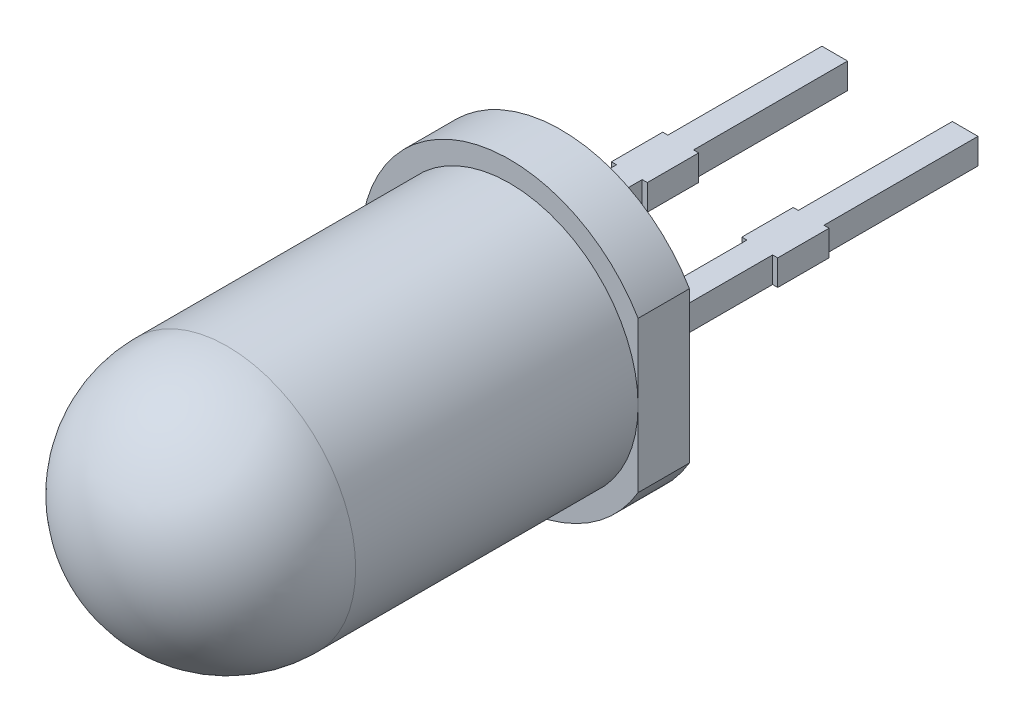
SolidWorks part; units mm, degrees
ref_plane "Front" through (0, 0, 0) normal (0, 0, 1) x (1, 0, 0)
ref_plane "Top" through (0, 0, 0) normal (0, 1, 0) x (1, 0, 0)
ref_plane "Right" through (0, 0, 0) normal (1, 0, 0) x (0, 0, -1)
sketch "Эскиз1" plane through (0, 0, 0) normal (0, -1, 0) x (1, 0, 0)
  line L0 (1.27, 0) -> (-1.27, 0) construction
  line L3 (-1.27, -3) -> (-1.27, 3.6) construction
  line L4 (-1.52, 3.6) -> (-1.52, 1)
  line L5 (-1.52, 1) -> (-1.62, 1)
  line L6 (-1.62, 1) -> (-1.62, 0)
  line L7 (-1.62, 0) -> (-1.52, 0)
  line L8 (-1.52, 0) -> (-1.52, -3)
  line L9 (-1.52, -3) -> (-1.02, -3)
  line L10 (-1.02, 1) -> (-1.02, 0) construction
  line L11 (-1.52, 1) -> (-1.52, 0) construction
  line L12 (-1.02, 0) -> (-1.02, -3)
  line L13 (-0.92, 0) -> (-1.02, 0)
  line L14 (-0.92, 1) -> (-0.92, 0)
  line L15 (-1.02, 1) -> (-0.92, 1)
  line L16 (-1.02, 3.6) -> (-1.02, 1)
  line L17 (1.52, 1) -> (1.52, 0) construction
  line L18 (1.02, 1) -> (1.02, 0) construction
  line L19 (1.02, 3.6) -> (1.02, 1)
  line L20 (1.02, 1) -> (0.92, 1)
  line L21 (0.92, 1) -> (0.92, 0)
  line L22 (0.92, 0) -> (1.02, 0)
  line L23 (1.02, 0) -> (1.02, -3)
  line L24 (1.52, -3) -> (1.02, -3)
  line L25 (1.52, 0) -> (1.52, -3)
  line L26 (1.62, 0) -> (1.52, 0)
  line L27 (1.62, 1) -> (1.62, 0)
  line L28 (1.52, 1) -> (1.62, 1)
  line L29 (1.52, 3.6) -> (1.52, 1)
  line L30 (1.27, -3) -> (1.27, 3.6) construction
  line L59 (-1.52, 3.6) -> (-1.02, 3.6)
  line L60 (1.02, 3.6) -> (1.52, 3.6)
  line L61 (-1.02, 3.6) -> (1.02, 3.6) construction
  point P19 (-1.27, -3)
  point P34 (1.27, -3)
  dimension "D4" = 2.6
  dimension "D1" = 0.5
  dimension "D2" = 2.54
  dimension "D3" = 0.7
  dimension "D5" = 1
  dimension "D6" = 3
extrude "Бобышка-Вытянуть1" add sketch "Эскиз1" along normal mid plane 0.5
sketch "Эскиз2" plane through (0, 0, 0) normal (0, 1, 0) x (1, 0, 0)
  line L0 (0, -3.6) -> (0, -12.6)
  line L1 (2.5, -10.1) -> (2.5, -4.6)
  line L2 (2.9, -3.6) -> (0, -3.6)
  line L3 (2.5, -4.6) -> (2.9, -4.6)
  line L4 (2.9, -4.6) -> (2.9, -3.6)
  line L5 (1.52, -3.6) -> (1.02, -3.6) construction
  line L6 (0, -3.6) -> (0, 0) construction
  arc A0 (2.5, -10.1) -> (0, -12.6) centre (0, -10.1) cw
  dimension "D1" = 5
  dimension "D2" = 5.8
  dimension "D3" = 1
  dimension "D4" = 9
revolve "Повернуть1" add sketch "Эскиз2" angle 360 about L6
sketch "Эскиз3" plane through (0, 0, 4.6) normal (0, 0, 1) x (1, 0, 0)
  line L0 (2.5, 1.4697) -> (2.5, -1.4697)
  circle A0 centre (0, 0) radius 2.5 construction
  circle A1 centre (0, 0) radius 2.9 construction
  arc A3 (2.5, 1.4697) -> (2.5, -1.4697) centre (0, 0) cw
extrude "Вырез-Вытянуть1" cut sketch "Эскиз3" against normal up to surface (1 mm away) up to face at (1.27, 0, 3.6)
